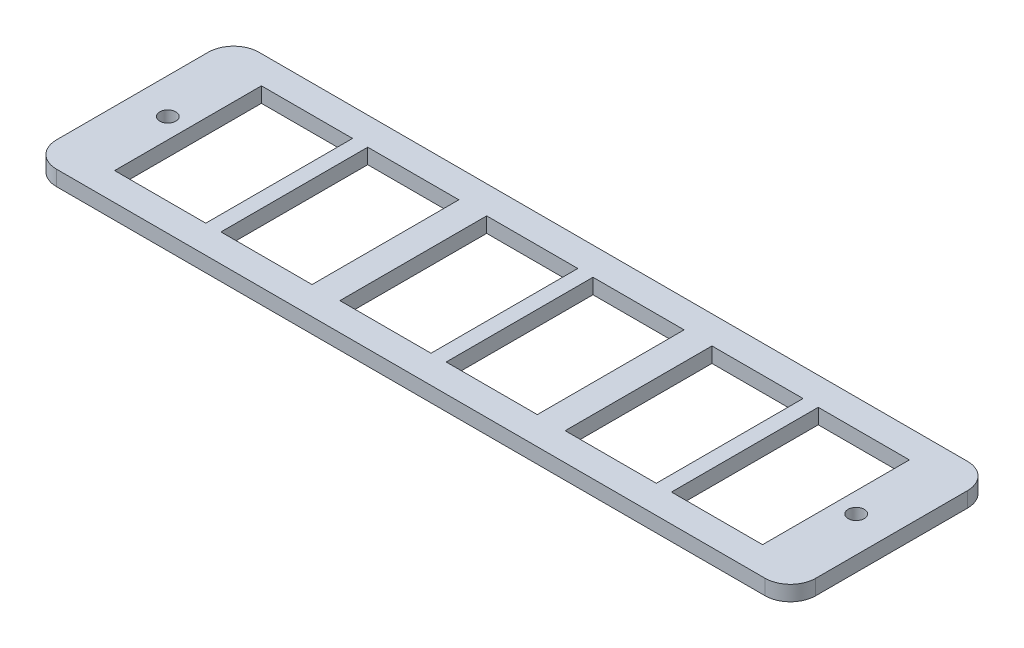
SolidWorks part; units mm, degrees
ref_plane "正面" through (0, 0, 0) normal (0, 0, 1) x (1, 0, 0)
ref_plane "平面" through (0, 0, 0) normal (0, 1, 0) x (1, 0, 0)
ref_plane "右側面" through (0, 0, 0) normal (1, 0, 0) x (0, 0, -1)
sketch "ｽｹｯﾁ1" plane through (0, 0, 0) normal (0, 1, 0) x (1, 0, 0)
  line L1 (0, 5) -> (150, 5)
  line L3 (0, 45) -> (150, 45)
  line L5 (29, 39.5) -> (29, 10.5)
  line L6 (29, 10.5) -> (11, 10.5)
  line L22 (11, 10.5) -> (11, 39.5)
  line L41 (11, 39.5) -> (29, 39.5)
  line L45 (50, 39.5) -> (50, 10.5)
  line L46 (50, 10.5) -> (32, 10.5)
  line L61 (32, 10.5) -> (32, 39.5)
  line L80 (32, 39.5) -> (50, 39.5)
  line L84 (75, 0) -> (75, 50) construction
  line L85 (55.5, 10.5) -> (55.5, 39.5)
  line L86 (73.5, 10.5) -> (55.5, 10.5)
  line L88 (73.5, 39.5) -> (73.5, 10.5)
  line L123 (55.5, 39.5) -> (73.5, 39.5)
  line L127 (150, 45) -> (150, 5)
  line L164 (76.5, 39.5) -> (76.5, 10.5)
  line L165 (94.5, 39.5) -> (76.5, 39.5)
  line L166 (76.5, 10.5) -> (94.5, 10.5)
  line L167 (94.5, 10.5) -> (94.5, 39.5)
  line L190 (118, 10.5) -> (118, 39.5)
  line L205 (100, 10.5) -> (118, 10.5)
  line L206 (100, 39.5) -> (100, 10.5)
  line L229 (139, 10.5) -> (139, 39.5)
  line L232 (118, 39.5) -> (100, 39.5)
  line L245 (121, 10.5) -> (139, 10.5)
  line L246 (121, 39.5) -> (121, 10.5)
  line L248 (139, 39.5) -> (121, 39.5)
  line L391 (0, 45) -> (0, 5)
  circle A0 centre (143, 25) radius 3 construction
  circle A3 centre (143, 25) radius 1.6
  circle A12 centre (7, 25) radius 1.6
  circle A14 centre (7, 25) radius 3 construction
  point P265 (75, 45)
  dimension "D3" = 2
extrude "ﾎﾞｽ - 押し出し1" add sketch "ｽｹｯﾁ1" along normal blind 3
fillet "ﾌｨﾚｯﾄ1" radius 5 4 edges at (150, 1.5, -5) (150, 1.5, -45) (0, 1.5, -5) (0, 1.5, -45)
